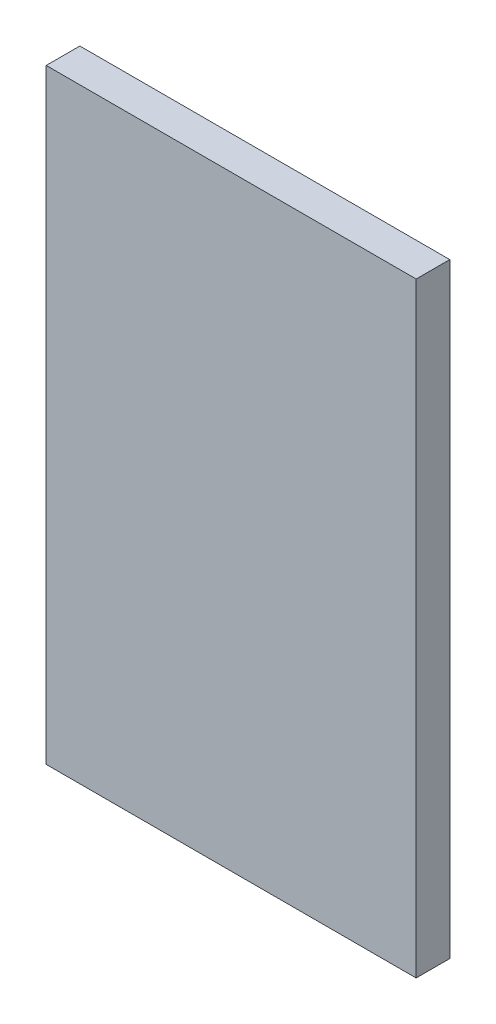
SolidWorks part; units mm, degrees
material "Бальса"
ref_plane "Спереди" through (0, 0, 0) normal (0, 0, 1) x (1, 0, 0)
ref_plane "Сверху" through (0, 0, 0) normal (0, 1, 0) x (1, 0, 0)
ref_plane "Справа" through (0, 0, 0) normal (1, 0, 0) x (0, 0, -1)
sketch "Эскиз1" plane through (0, 0, 0) normal (0, 0, 1) x (1, 0, 0)
  line L1 (0, 0) -> (550, 0)
  line L2 (0, 0) -> (0, 900)
  line L3 (0, 900) -> (550, 900)
  line L4 (550, 0) -> (550, 900)
  dimension "D1" = 550
  dimension "D2" = 900
extrude "Бобышка-Вытянуть1" add sketch "Эскиз1" along normal blind 50
